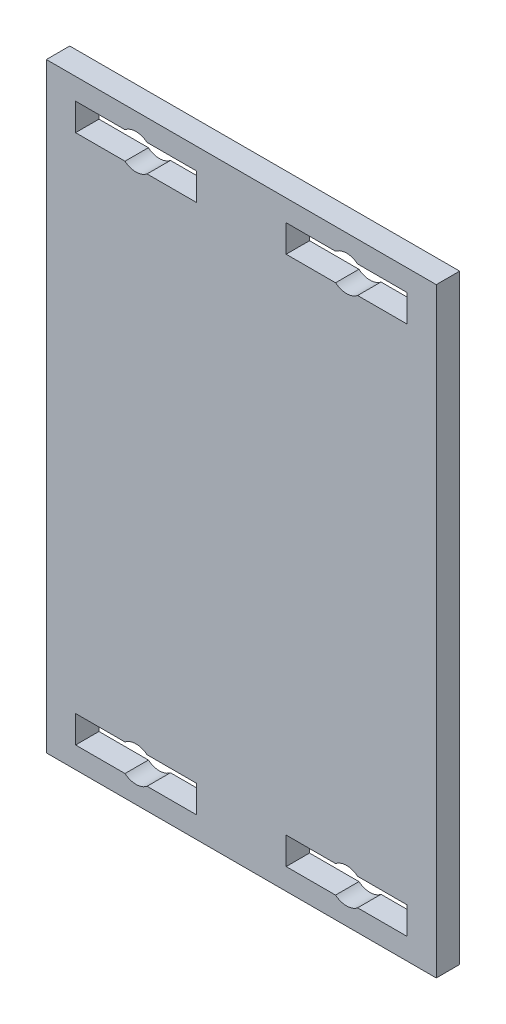
SolidWorks part; units mm, degrees
ref_plane "前视基准面" through (0, 0, 0) normal (0, 0, 1) x (1, 0, 0)
ref_plane "上视基准面" through (0, 0, 0) normal (0, 1, 0) x (1, 0, 0)
ref_plane "右视基准面" through (0, 0, 0) normal (1, 0, 0) x (0, 0, -1)
sketch "草图1" plane through (0, 0, 0) normal (0, 0, 1) x (1, 0, 0)
  line L0 (0, -1000) -> (0, 49000) construction
  line L1 (-25, 38.5) -> (25, 38.5)
  line L2 (-25, 38.5) -> (-25, -38.5)
  line L3 (-25, -38.5) -> (25, -38.5)
  line L4 (25, 38.5) -> (25, -38.5)
  line L5 (-25, 38.5) -> (25, -38.5) construction
  line L6 (-25, -38.5) -> (25, 38.5) construction
  line L7 (-13.5, 34) -> (13.5, 34) construction
  line L8 (-13.5, 34) -> (-13.5, -34) construction
  line L9 (-13.5, -34) -> (13.5, -34) construction
  line L10 (13.5, 34) -> (13.5, -34) construction
  line L11 (-13.5, 34) -> (13.5, -34) construction
  line L12 (-13.5, -34) -> (13.5, 34) construction
  line L13 (-1002, 0) -> (48998, 0) construction
  line L14 (-12.0858, 32.25) -> (-5.75, 32.25)
  line L15 (-21.25, 35.75) -> (-14.9142, 35.75)
  line L16 (-21.25, 35.75) -> (-21.25, 32.25)
  line L17 (-21.25, 32.25) -> (-14.9142, 32.25)
  line L18 (-5.75, 35.75) -> (-5.75, 32.25)
  line L19 (-21.25, 35.75) -> (-5.75, 32.25) construction
  line L20 (-21.25, 32.25) -> (-5.75, 35.75) construction
  line L21 (-12.0858, 35.75) -> (-5.75, 35.75)
  line L22 (21.25, 35.75) -> (21.25, 32.25)
  line L23 (21.25, 35.75) -> (14.9142, 35.75)
  line L24 (12.0858, 35.75) -> (5.75, 35.75)
  line L25 (5.75, 35.75) -> (5.75, 32.25)
  line L26 (12.0858, 32.25) -> (5.75, 32.25)
  line L27 (21.25, 32.25) -> (14.9142, 32.25)
  line L28 (21.25, -35.75) -> (14.9142, -35.75)
  line L29 (12.0858, -35.75) -> (5.75, -35.75)
  line L30 (5.75, -35.75) -> (5.75, -32.25)
  line L31 (12.0858, -32.25) -> (5.75, -32.25)
  line L32 (21.25, -32.25) -> (14.9142, -32.25)
  line L33 (21.25, -35.75) -> (21.25, -32.25)
  line L34 (-21.25, -35.75) -> (-21.25, -32.25)
  line L35 (-21.25, -35.75) -> (-14.9142, -35.75)
  line L36 (-12.0858, -35.75) -> (-5.75, -35.75)
  line L37 (-5.75, -35.75) -> (-5.75, -32.25)
  line L38 (-12.0858, -32.25) -> (-5.75, -32.25)
  line L39 (-21.25, -32.25) -> (-14.9142, -32.25)
  arc A0 (-14.9142, 32.25) -> (-12.0858, 32.25) centre (-13.5, 34) ccw
  arc A1 (-12.0858, 35.75) -> (-14.9142, 35.75) centre (-13.5, 34) ccw
  arc A2 (12.0858, 35.75) -> (14.9142, 35.75) centre (13.5, 34) cw
  arc A3 (14.9142, 32.25) -> (12.0858, 32.25) centre (13.5, 34) cw
  arc A4 (12.0858, -35.75) -> (14.9142, -35.75) centre (13.5, -34) ccw
  arc A5 (14.9142, -32.25) -> (12.0858, -32.25) centre (13.5, -34) ccw
  arc A6 (-12.0858, -35.75) -> (-14.9142, -35.75) centre (-13.5, -34) cw
  arc A7 (-14.9142, -32.25) -> (-12.0858, -32.25) centre (-13.5, -34) cw
  point P0 (0, 0)
  point P5 (0, 0)
  dimension "D7" = 4.5
  dimension "D1" = 77
  dimension "D2" = 50
  dimension "D3" = 68
  dimension "D4" = 27
  dimension "D5" = 3.5
  dimension "D6" = 15.5
extrude "凸台-拉伸1" add sketch "草图1" along normal blind 3
